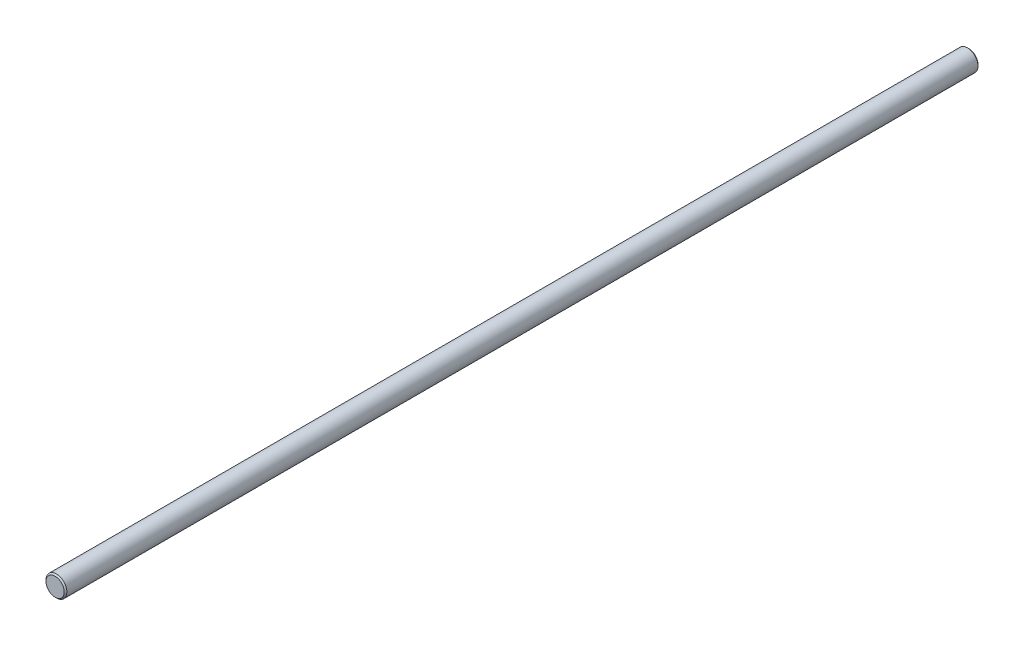
SolidWorks part; units mm, degrees
material "1023 Arkusz stali węglowej (SS)"
ref_plane "Płaszczyzna przednia" through (0, 0, 0) normal (0, 0, 1) x (1, 0, 0)
ref_plane "Płaszczyzna górna" through (0, 0, 0) normal (0, 1, 0) x (1, 0, 0)
ref_plane "Płaszczyzna prawa" through (0, 0, 0) normal (1, 0, 0) x (0, 0, -1)
sketch "Szkic1" plane through (0, 0, 0) normal (0, 0, 1) x (1, 0, 0)
  circle A0 centre (0, 0) radius 4
  dimension "D1" = 8
extrude "Dodanie-wyciągnięcie1" add sketch "Szkic1" along normal blind 350
chamfer "Sfazowanie1" distance 0.5 angle 45 2 edges at (4, 0, 350) (4, 0, 0)
